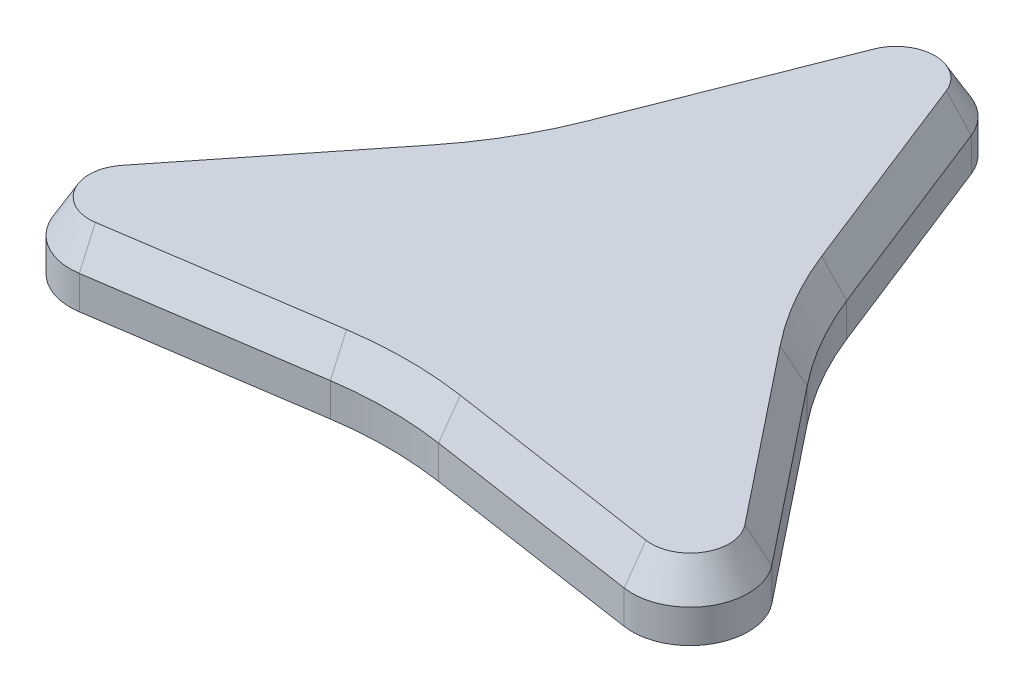
SolidWorks part; units mm, degrees
ref_plane "Front Plane" through (0, 0, 0) normal (0, 0, 1) x (1, 0, 0)
ref_plane "Top Plane" through (0, 0, 0) normal (0, 1, 0) x (1, 0, 0)
ref_plane "Right Plane" through (0, 0, 0) normal (1, 0, 0) x (0, 0, -1)
sketch "Sketch1" plane through (0, 0, 0) normal (0, 1, 0) x (1, 0, 0)
  line L0 (0, 0) -> (-68.3868, -39.4831) construction
  line L1 (0, 0) -> (0, 74.7926) construction
  line L2 (0, 0) -> (79.4724, -45.8834) construction
  line L3 (-6.5, 41.5729) -> (-16.2217, 16.8712)
  line L4 (6.5, 41.5729) -> (16.2217, 16.8712)
  line L5 (39.2532, -15.1573) -> (22.7217, 5.6128)
  line L6 (32.7532, -26.4156) -> (6.5, -22.484)
  line L7 (-32.7532, -26.4156) -> (-6.5, -22.484)
  line L8 (-39.2532, -15.1573) -> (-22.7217, 5.6128)
  arc A1 (-6.5, 41.5729) -> (6.5, 41.5729) centre (0, 39.0147) cw
  arc A2 (-16.2217, 16.8712) -> (-19.0526, 11) centre (-57.0604, 32.9438) cw
  arc A3 (16.2217, 16.8712) -> (19.0526, 11) centre (57.0604, 32.9438) ccw
  arc A4 (39.2532, -15.1573) -> (32.7532, -26.4156) centre (33.7877, -19.5074) cw
  arc A5 (22.7217, 5.6128) -> (19.0526, 11) centre (57.0604, 32.9438) cw
  arc A6 (6.5, -22.484) -> (0, -22) centre (0, -65.8877) ccw
  arc A7 (-32.7532, -26.4156) -> (-39.2532, -15.1573) centre (-33.7877, -19.5074) cw
  arc A8 (-6.5, -22.484) -> (0, -22) centre (0, -65.8877) cw
  arc A9 (-22.7217, 5.6128) -> (-19.0526, 11) centre (-57.0604, 32.9438) ccw
  dimension "D3" = 22
  dimension "D6" = 6.9853
  dimension "D4" = 39.0147
  dimension "D1" = 60
  dimension "D2" = 60
  dimension "D5" = 6.5
  dimension "D7" = 6.5
extrude "Extrude2" add sketch "Sketch1" along normal blind 8
chamfer "Chamfer2" distance 4 angle 30 12 edges at (11.3609, 8, -29.222) (0, 8, -46) (19.0526, 8, -11) (-11.3609, 8, -29.222) (30.9874, 8, 4.7722) (-19.0526, 8, -11) (39.8372, 8, 23) (-30.9874, 8, 4.7722) (19.6266, 8, 24.4498) (-39.8372, 8, 23) (0, 8, 22) (-19.6266, 8, 24.4498)
sketch "Sketch2" plane through (0, 0, 0) normal (0, 1, 0) x (1, 0, 0)
  line L1 (173205.0808, 100000) -> (-173273.4675, -100039.4831) construction
  line L2 (-22.7213, -13.1182) -> (-42.235, -24.3844) construction
  arc A0 (-33.1351, -24.4646) -> (-37.7545, -16.4635) centre (-33.7877, -19.5074) cw
  arc A1 (-33.3962, -22.4817) -> (-36.1678, -17.6811) centre (-33.7877, -19.5074) cw
  arc A2 (-37.7545, -16.4635) -> (-36.1678, -17.6811) centre (-36.9611, -17.0723) cw
  arc A3 (-33.1351, -24.4646) -> (-33.3962, -22.4817) centre (-33.2656, -23.4731) ccw
  arc A4 (-4.6194, 40.9281) -> (4.6194, 40.9281) centre (0, 39.0147) cw
  arc A5 (-2.7716, 40.1628) -> (2.7716, 40.1628) centre (0, 39.0147) cw
  arc A6 (4.6194, 40.9281) -> (2.7716, 40.1628) centre (3.6955, 40.5454) cw
  arc A7 (-4.6194, 40.9281) -> (-2.7716, 40.1628) centre (-3.6955, 40.5454) ccw
  arc A8 (37.7545, -16.4635) -> (33.1351, -24.4646) centre (33.7877, -19.5074) cw
  arc A9 (36.1678, -17.6811) -> (33.3962, -22.4817) centre (33.7877, -19.5074) cw
  arc A10 (33.1351, -24.4646) -> (33.3962, -22.4817) centre (33.2656, -23.4731) cw
  arc A11 (37.7545, -16.4635) -> (36.1678, -17.6811) centre (36.9611, -17.0723) ccw
  dimension "D1" = 1
  dimension "D3" = 135
  dimension "D2" = 5
extrude "Cut-Extrude1" cut sketch "Sketch2" along normal blind 3
